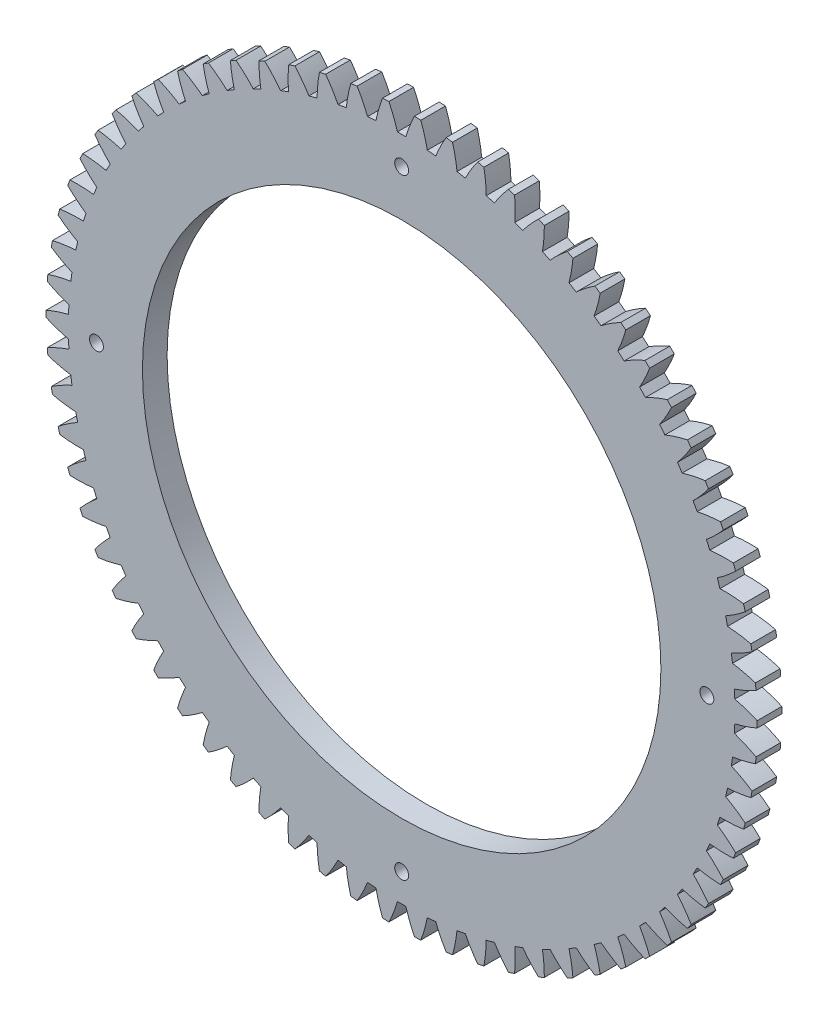
SolidWorks part; units mm, degrees
ref_plane "Front Plane" through (0, 0, 0) normal (0, 0, 1) x (1, 0, 0)
ref_plane "Top Plane" through (0, 0, 0) normal (0, 1, 0) x (1, 0, 0)
ref_plane "Right Plane" through (0, 0, 0) normal (1, 0, 0) x (0, 0, -1)
sketch "Sketch1" plane through (0, 0, 0) normal (0, 0, 1) x (1, 0, 0)
  point P0 (0, 0)
  circle B0 centre (78.5, 0) radius 1.7859
  circle B1 centre (0, -78.5) radius 1.7859
  circle B2 centre (0, 0) radius 66.675
  circle B3 centre (-78.5, 0) radius 1.7859
  circle B4 centre (0, 78.5) radius 1.7859
  arc B5 (-91.4363, -0.8211) -> (-85.6793, -2.7591) centre (-77.2542, 31.7884) ccw
  arc B6 (-85.6793, -2.7591) -> (-85.5817, -4.9322) centre (0, 0) ccw
  arc B7 (-85.5817, -4.9322) -> (-91.1418, -7.3785) centre (-74.0937, -38.5855) ccw
  arc B8 (-91.1418, -7.3785) -> (-90.9946, -9.0141) centre (0, 0) ccw
  arc B9 (-90.9946, -9.0141) -> (-85.0871, -10.4282) centre (-79.7927, 24.7354) ccw
  arc B10 (-85.0871, -10.4282) -> (-84.7951, -12.5839) centre (0, 0) ccw
  arc B11 (-84.7951, -12.5839) -> (-90.1135, -15.5187) centre (-70.3366, -45.0718) ccw
  arc B12 (-90.1135, -15.5187) -> (-89.8203, -17.1345) centre (0, 0) ccw
  arc B13 (-89.8203, -17.1345) -> (-83.8098, -18.0134) centre (-81.6887, 17.4833) ccw
  arc B14 (-83.8098, -18.0134) -> (-83.3257, -20.1342) centre (0, 0) ccw
  arc B15 (-83.3257, -20.1342) -> (-88.3597, -23.5339) centre (-66.0133, -51.1953) ccw
  arc B16 (-88.3597, -23.5339) -> (-87.9228, -25.1169) centre (0, 0) ccw
  arc B17 (-87.9228, -25.1169) -> (-81.8577, -25.4535) centre (-82.927, 10.0904) ccw
  arc B18 (-81.8577, -25.4535) -> (-81.1854, -27.5224) centre (0, 0) ccw
  arc B19 (-81.1854, -27.5224) -> (-85.8944, -31.3597) centre (-61.1584, -56.9066) ccw
  arc B20 (-85.8944, -31.3597) -> (-85.3174, -32.8972) centre (0, 0) ccw
  arc B21 (-85.3174, -32.8972) -> (-79.2465, -32.6887) centre (-83.4977, 2.6163) ccw
  arc B22 (-79.2465, -32.6887) -> (-78.3915, -34.689) centre (0, 0) ccw
  arc B23 (-78.3915, -34.689) -> (-82.7375, -38.9329) centre (-55.8111, -62.1597) ccw
  arc B24 (-82.7375, -38.9329) -> (-82.025, -40.4125) centre (0, 0) ccw
  arc B25 (-82.025, -40.4125) -> (-75.9973, -39.6607) centre (-83.3961, -4.879) ccw
  arc B26 (-75.9973, -39.6607) -> (-74.9664, -41.5763) centre (0, 0) ccw
  arc B27 (-74.9664, -41.5763) -> (-78.9145, -46.1928) centre (-50.0145, -66.9123) ccw
  arc B28 (-78.9145, -46.1928) -> (-78.0723, -47.6025) centre (0, 0) ccw
  arc B29 (-78.0723, -47.6025) -> (-72.1362, -46.3134) centre (-82.623, -12.3349) ccw
  arc B30 (-72.1362, -46.3134) -> (-70.9378, -48.1289) centre (0, 0) ccw
  arc B31 (-70.9378, -48.1289) -> (-74.4562, -53.0806) centre (-43.8152, -71.1262) ccw
  arc B32 (-74.4562, -53.0806) -> (-73.4909, -54.4092) centre (0, 0) ccw
  arc B33 (-73.4909, -54.4092) -> (-67.6943, -52.5932) centre (-81.1847, -19.6915) ccw
  arc B34 (-67.6943, -52.5932) -> (-66.338, -54.2939) centre (0, 0) ccw
  arc B35 (-66.338, -54.2939) -> (-69.3983, -59.5411) centre (-37.2631, -74.7675) ccw
  arc B36 (-69.3983, -59.5411) -> (-68.3178, -60.7778) centre (0, 0) ccw
  arc B37 (-68.3178, -60.7778) -> (-62.7073, -58.4495) centre (-79.0927, -26.8896) ccw
  arc B38 (-62.7073, -58.4495) -> (-61.204, -60.0219) centre (0, 0) ccw
  arc B39 (-61.204, -60.0219) -> (-63.7817, -65.5223) centre (-30.411, -77.8067) ccw
  arc B40 (-63.7817, -65.5223) -> (-62.5947, -66.6571) centre (0, 0) ccw
  arc B41 (-62.5947, -66.6571) -> (-57.2155, -63.8353) centre (-76.364, -33.8711) ccw
  arc B42 (-57.2155, -63.8353) -> (-55.5773, -65.2665) centre (0, 0) ccw
  arc B43 (-55.5773, -65.2665) -> (-57.6516, -70.9758) centre (-23.314, -80.2195) ccw
  arc B44 (-57.6516, -70.9758) -> (-56.3677, -71.9997) centre (0, 0) ccw
  arc B45 (-56.3677, -71.9997) -> (-51.263, -68.7071) centre (-73.0204, -40.58) ccw
  arc B46 (-51.263, -68.7071) -> (-49.5031, -69.9857) centre (0, 0) ccw
  arc B47 (-49.5031, -69.9857) -> (-51.0573, -75.858) centre (-16.0293, -81.9864) ccw
  arc B48 (-51.0573, -75.858) -> (-49.6867, -76.7626) centre (0, 0) ccw
  arc B49 (-49.6867, -76.7626) -> (-44.8978, -73.0256) centre (-69.0889, -46.9621) ccw
  arc B50 (-44.8978, -73.0256) -> (-43.0304, -74.1414) centre (0, 0) ccw
  arc B51 (-43.0304, -74.1414) -> (-44.0519, -80.1293) centre (-8.6156, -83.0932) ccw
  arc B52 (-44.0519, -80.1293) -> (-42.6058, -80.9075) centre (0, 0) ccw
  arc B53 (-42.6058, -80.9075) -> (-38.1711, -76.7563) centre (-64.6011, -52.9661) ccw
  arc B54 (-38.1711, -76.7563) -> (-36.2112, -77.7001) centre (0, 0) ccw
  arc B55 (-36.2112, -77.7001) -> (-36.6918, -83.7555) centre (-1.1325, -83.531) ccw
  arc B56 (-36.6918, -83.7555) -> (-35.1817, -84.4009) centre (0, 0) ccw
  arc B57 (-35.1817, -84.4009) -> (-31.1371, -79.8689) centre (-59.5932, -58.5437) ccw
  arc B58 (-31.1371, -79.8689) -> (-29.1004, -80.6333) centre (0, 0) ccw
  arc B59 (-29.1004, -80.6333) -> (-29.0363, -86.7074) centre (6.3597, -83.2962) ccw
  arc B60 (-29.0363, -86.7074) -> (-27.4745, -87.2148) centre (0, 0) ccw
  arc B61 (-27.4745, -87.2148) -> (-23.8523, -82.3385) centre (-54.1054, -63.6499) ccw
  arc B62 (-23.8523, -82.3385) -> (-21.7554, -82.9172) centre (0, 0) ccw
  arc B63 (-21.7554, -82.9172) -> (-21.147, -88.9611) centre (13.8007, -82.3908) ccw
  arc B64 (-21.147, -88.9611) -> (-19.546, -89.3265) centre (0, 0) ccw
  arc B65 (-19.546, -89.3265) -> (-16.3755, -84.1451) centre (-48.1821, -68.2437) ccw
  arc B66 (-16.3755, -84.1451) -> (-14.2351, -84.5335) centre (0, 0) ccw
  arc B67 (-14.2351, -84.5335) -> (-13.0875, -90.4986) centre (21.1306, -80.8221) ccw
  arc B68 (-13.0875, -90.4986) -> (-11.4601, -90.719) centre (0, 0) ccw
  arc B69 (-11.4601, -90.719) -> (-8.7669, -85.2743) centre (-41.8708, -72.2879) ccw
  arc B70 (-8.7669, -85.2743) -> (-6.6003, -85.4693) centre (0, 0) ccw
  arc B71 (-6.6003, -85.4693) -> (-4.9225, -91.3074) centre (28.2904, -78.6026) ccw
  arc B72 (-4.9225, -91.3074) -> (-3.282, -91.3811) centre (0, 0) ccw
  arc B73 (-3.282, -91.3811) -> (-1.0877, -85.7168) centre (-35.2224, -75.7502) ccw
  arc B74 (-1.0877, -85.7168) -> (1.0877, -85.7168) centre (0, 0) ccw
  arc B75 (1.0877, -85.7168) -> (3.282, -91.3811) centre (35.2224, -75.7502) ccw
  arc B76 (3.282, -91.3811) -> (4.9225, -91.3074) centre (0, 0) ccw
  arc B77 (4.9225, -91.3074) -> (6.6003, -85.4693) centre (-28.2904, -78.6026) ccw
  arc B78 (6.6003, -85.4693) -> (8.7669, -85.2743) centre (0, 0) ccw
  arc B79 (8.7669, -85.2743) -> (11.4601, -90.719) centre (41.8708, -72.2879) ccw
  arc B80 (11.4601, -90.719) -> (13.0875, -90.4986) centre (0, 0) ccw
  arc B81 (13.0875, -90.4986) -> (14.2351, -84.5335) centre (-21.1306, -80.8221) ccw
  arc B82 (14.2351, -84.5335) -> (16.3755, -84.1451) centre (0, 0) ccw
  arc B83 (16.3755, -84.1451) -> (19.546, -89.3265) centre (48.1821, -68.2437) ccw
  arc B84 (19.546, -89.3265) -> (21.147, -88.9611) centre (0, 0) ccw
  arc B85 (21.147, -88.9611) -> (21.7554, -82.9172) centre (-13.8007, -82.3908) ccw
  arc B86 (21.7554, -82.9172) -> (23.8523, -82.3385) centre (0, 0) ccw
  arc B87 (23.8523, -82.3385) -> (27.4745, -87.2148) centre (54.1054, -63.6499) ccw
  arc B88 (27.4745, -87.2148) -> (29.0363, -86.7074) centre (0, 0) ccw
  arc B89 (29.0363, -86.7074) -> (29.1004, -80.6333) centre (-6.3597, -83.2962) ccw
  arc B90 (29.1004, -80.6333) -> (31.1371, -79.8689) centre (0, 0) ccw
  arc B91 (31.1371, -79.8689) -> (35.1817, -84.4009) centre (59.5932, -58.5437) ccw
  arc B92 (35.1817, -84.4009) -> (36.6918, -83.7555) centre (0, 0) ccw
  arc B93 (36.6918, -83.7555) -> (36.2112, -77.7001) centre (1.1325, -83.531) ccw
  arc B94 (36.2112, -77.7001) -> (38.1711, -76.7563) centre (0, 0) ccw
  arc B95 (38.1711, -76.7563) -> (42.6058, -80.9075) centre (64.6011, -52.9661) ccw
  arc B96 (42.6058, -80.9075) -> (44.0519, -80.1293) centre (0, 0) ccw
  arc B97 (44.0519, -80.1293) -> (43.0304, -74.1414) centre (8.6156, -83.0932) ccw
  arc B98 (43.0304, -74.1414) -> (44.8978, -73.0256) centre (0, 0) ccw
  arc B99 (44.8978, -73.0256) -> (49.6867, -76.7626) centre (69.0889, -46.9621) ccw
  arc B100 (49.6867, -76.7626) -> (51.0573, -75.858) centre (0, 0) ccw
  arc B101 (51.0573, -75.858) -> (49.5031, -69.9857) centre (16.0293, -81.9864) ccw
  arc B102 (49.5031, -69.9857) -> (51.263, -68.7071) centre (0, 0) ccw
  arc B103 (51.263, -68.7071) -> (56.3677, -71.9997) centre (73.0204, -40.58) ccw
  arc B104 (56.3677, -71.9997) -> (57.6516, -70.9758) centre (0, 0) ccw
  arc B105 (57.6516, -70.9758) -> (55.5773, -65.2665) centre (23.314, -80.2195) ccw
  arc B106 (55.5773, -65.2665) -> (57.2155, -63.8353) centre (0, 0) ccw
  arc B107 (57.2155, -63.8353) -> (62.5947, -66.6571) centre (76.364, -33.8711) ccw
  arc B108 (62.5947, -66.6571) -> (63.7817, -65.5223) centre (0, 0) ccw
  arc B109 (63.7817, -65.5223) -> (61.204, -60.0219) centre (30.411, -77.8067) ccw
  arc B110 (61.204, -60.0219) -> (62.7073, -58.4495) centre (0, 0) ccw
  arc B111 (62.7073, -58.4495) -> (68.3178, -60.7778) centre (79.0927, -26.8896) ccw
  arc B112 (68.3178, -60.7778) -> (69.3983, -59.5411) centre (0, 0) ccw
  arc B113 (69.3983, -59.5411) -> (66.338, -54.2939) centre (37.2631, -74.7675) ccw
  arc B114 (66.338, -54.2939) -> (67.6943, -52.5932) centre (0, 0) ccw
  arc B115 (67.6943, -52.5932) -> (73.4909, -54.4092) centre (81.1847, -19.6915) ccw
  arc B116 (73.4909, -54.4092) -> (74.4562, -53.0806) centre (0, 0) ccw
  arc B117 (74.4562, -53.0806) -> (70.9378, -48.1289) centre (43.8152, -71.1262) ccw
  arc B118 (70.9378, -48.1289) -> (72.1362, -46.3134) centre (0, 0) ccw
  arc B119 (72.1362, -46.3134) -> (78.0723, -47.6025) centre (82.623, -12.3349) ccw
  arc B120 (78.0723, -47.6025) -> (78.9145, -46.1928) centre (0, 0) ccw
  arc B121 (78.9145, -46.1928) -> (74.9664, -41.5763) centre (50.0145, -66.9123) ccw
  arc B122 (74.9664, -41.5763) -> (75.9973, -39.6607) centre (0, 0) ccw
  arc B123 (75.9973, -39.6607) -> (82.025, -40.4125) centre (83.3961, -4.879) ccw
  arc B124 (82.025, -40.4125) -> (82.7375, -38.9329) centre (0, 0) ccw
  arc B125 (82.7375, -38.9329) -> (78.3915, -34.689) centre (55.8111, -62.1597) ccw
  arc B126 (78.3915, -34.689) -> (79.2465, -32.6887) centre (0, 0) ccw
  arc B127 (79.2465, -32.6887) -> (85.3174, -32.8972) centre (83.4977, 2.6163) ccw
  arc B128 (85.3174, -32.8972) -> (85.8944, -31.3597) centre (0, 0) ccw
  arc B129 (85.8944, -31.3597) -> (81.1854, -27.5224) centre (61.1584, -56.9066) ccw
  arc B130 (81.1854, -27.5224) -> (81.8577, -25.4535) centre (0, 0) ccw
  arc B131 (81.8577, -25.4535) -> (87.9228, -25.1169) centre (82.927, 10.0904) ccw
  arc B132 (87.9228, -25.1169) -> (88.3597, -23.5339) centre (0, 0) ccw
  arc B133 (88.3597, -23.5339) -> (83.3257, -20.1342) centre (66.0133, -51.1953) ccw
  arc B134 (83.3257, -20.1342) -> (83.8098, -18.0134) centre (0, 0) ccw
  arc B135 (83.8098, -18.0134) -> (89.8203, -17.1345) centre (81.6887, 17.4833) ccw
  arc B136 (89.8203, -17.1345) -> (90.1135, -15.5187) centre (0, 0) ccw
  arc B137 (90.1135, -15.5187) -> (84.7951, -12.5839) centre (70.3366, -45.0718) ccw
  arc B138 (84.7951, -12.5839) -> (85.0871, -10.4282) centre (0, 0) ccw
  arc B139 (85.0871, -10.4282) -> (90.9946, -9.0141) centre (79.7927, 24.7354) ccw
  arc B140 (90.9946, -9.0141) -> (91.1418, -7.3785) centre (0, 0) ccw
  arc B141 (91.1418, -7.3785) -> (85.5817, -4.9322) centre (74.0937, -38.5855) ccw
  arc B142 (85.5817, -4.9322) -> (85.6793, -2.7591) centre (0, 0) ccw
  arc B143 (85.6793, -2.7591) -> (91.4363, -0.8211) centre (77.2542, 31.7884) ccw
  arc B144 (91.4363, -0.8211) -> (91.4363, 0.8211) centre (0, 0) ccw
  arc B145 (91.4363, 0.8211) -> (85.6793, 2.7591) centre (77.2542, -31.7884) ccw
  arc B146 (85.6793, 2.7591) -> (85.5817, 4.9322) centre (0, 0) ccw
  arc B147 (85.5817, 4.9322) -> (91.1418, 7.3785) centre (74.0937, 38.5855) ccw
  arc B148 (91.1418, 7.3785) -> (90.9946, 9.0141) centre (0, 0) ccw
  arc B149 (90.9946, 9.0141) -> (85.0871, 10.4282) centre (79.7927, -24.7354) ccw
  arc B150 (85.0871, 10.4282) -> (84.7951, 12.5839) centre (0, 0) ccw
  arc B151 (84.7951, 12.5839) -> (90.1135, 15.5187) centre (70.3366, 45.0718) ccw
  arc B152 (90.1135, 15.5187) -> (89.8203, 17.1345) centre (0, 0) ccw
  arc B153 (89.8203, 17.1345) -> (83.8098, 18.0134) centre (81.6887, -17.4833) ccw
  arc B154 (83.8098, 18.0134) -> (83.3257, 20.1342) centre (0, 0) ccw
  arc B155 (83.3257, 20.1342) -> (88.3597, 23.5339) centre (66.0133, 51.1953) ccw
  arc B156 (88.3597, 23.5339) -> (87.9228, 25.1169) centre (0, 0) ccw
  arc B157 (87.9228, 25.1169) -> (81.8577, 25.4535) centre (82.927, -10.0904) ccw
  arc B158 (81.8577, 25.4535) -> (81.1854, 27.5224) centre (0, 0) ccw
  arc B159 (81.1854, 27.5224) -> (85.8944, 31.3597) centre (61.1584, 56.9066) ccw
  arc B160 (85.8944, 31.3597) -> (85.3174, 32.8972) centre (0, 0) ccw
  arc B161 (85.3174, 32.8972) -> (79.2465, 32.6887) centre (83.4977, -2.6163) ccw
  arc B162 (79.2465, 32.6887) -> (78.3915, 34.689) centre (0, 0) ccw
  arc B163 (78.3915, 34.689) -> (82.7375, 38.9329) centre (55.8111, 62.1597) ccw
  arc B164 (82.7375, 38.9329) -> (82.025, 40.4125) centre (0, 0) ccw
  arc B165 (82.025, 40.4125) -> (75.9973, 39.6607) centre (83.3961, 4.879) ccw
  arc B166 (75.9973, 39.6607) -> (74.9664, 41.5763) centre (0, 0) ccw
  arc B167 (74.9664, 41.5763) -> (78.9145, 46.1928) centre (50.0145, 66.9123) ccw
  arc B168 (78.9145, 46.1928) -> (78.0723, 47.6025) centre (0, 0) ccw
  arc B169 (78.0723, 47.6025) -> (72.1362, 46.3134) centre (82.623, 12.3349) ccw
  arc B170 (72.1362, 46.3134) -> (70.9378, 48.1289) centre (0, 0) ccw
  arc B171 (70.9378, 48.1289) -> (74.4562, 53.0806) centre (43.8152, 71.1262) ccw
  arc B172 (74.4562, 53.0806) -> (73.4909, 54.4092) centre (0, 0) ccw
  arc B173 (73.4909, 54.4092) -> (67.6943, 52.5932) centre (81.1847, 19.6915) ccw
  arc B174 (67.6943, 52.5932) -> (66.338, 54.2939) centre (0, 0) ccw
  arc B175 (66.338, 54.2939) -> (69.3983, 59.5411) centre (37.2631, 74.7675) ccw
  arc B176 (69.3983, 59.5411) -> (68.3178, 60.7778) centre (0, 0) ccw
  arc B177 (68.3178, 60.7778) -> (62.7073, 58.4495) centre (79.0927, 26.8896) ccw
  arc B178 (62.7073, 58.4495) -> (61.204, 60.0219) centre (0, 0) ccw
  arc B179 (61.204, 60.0219) -> (63.7817, 65.5223) centre (30.411, 77.8067) ccw
  arc B180 (63.7817, 65.5223) -> (62.5947, 66.6571) centre (0, 0) ccw
  arc B181 (62.5947, 66.6571) -> (57.2155, 63.8353) centre (76.364, 33.8711) ccw
  arc B182 (57.2155, 63.8353) -> (55.5773, 65.2665) centre (0, 0) ccw
  arc B183 (55.5773, 65.2665) -> (57.6516, 70.9758) centre (23.314, 80.2195) ccw
  arc B184 (57.6516, 70.9758) -> (56.3677, 71.9997) centre (0, 0) ccw
  arc B185 (56.3677, 71.9997) -> (51.263, 68.7071) centre (73.0204, 40.58) ccw
  arc B186 (51.263, 68.7071) -> (49.5031, 69.9857) centre (0, 0) ccw
  arc B187 (49.5031, 69.9857) -> (51.0573, 75.858) centre (16.0293, 81.9864) ccw
  arc B188 (51.0573, 75.858) -> (49.6867, 76.7626) centre (0, 0) ccw
  arc B189 (49.6867, 76.7626) -> (44.8978, 73.0256) centre (69.0889, 46.9621) ccw
  arc B190 (44.8978, 73.0256) -> (43.0304, 74.1414) centre (0, 0) ccw
  arc B191 (43.0304, 74.1414) -> (44.0519, 80.1293) centre (8.6156, 83.0932) ccw
  arc B192 (44.0519, 80.1293) -> (42.6058, 80.9075) centre (0, 0) ccw
  arc B193 (42.6058, 80.9075) -> (38.1711, 76.7563) centre (64.6011, 52.9661) ccw
  arc B194 (38.1711, 76.7563) -> (36.2112, 77.7001) centre (0, 0) ccw
  arc B195 (36.2112, 77.7001) -> (36.6918, 83.7555) centre (1.1325, 83.531) ccw
  arc B196 (36.6918, 83.7555) -> (35.1817, 84.4009) centre (0, 0) ccw
  arc B197 (35.1817, 84.4009) -> (31.1371, 79.8689) centre (59.5932, 58.5437) ccw
  arc B198 (31.1371, 79.8689) -> (29.1004, 80.6333) centre (0, 0) ccw
  arc B199 (29.1004, 80.6333) -> (29.0363, 86.7074) centre (-6.3597, 83.2962) ccw
  arc B200 (29.0363, 86.7074) -> (27.4745, 87.2148) centre (0, 0) ccw
  arc B201 (27.4745, 87.2148) -> (23.8523, 82.3385) centre (54.1054, 63.6499) ccw
  arc B202 (23.8523, 82.3385) -> (21.7554, 82.9172) centre (0, 0) ccw
  arc B203 (21.7554, 82.9172) -> (21.147, 88.9611) centre (-13.8007, 82.3908) ccw
  arc B204 (21.147, 88.9611) -> (19.546, 89.3265) centre (0, 0) ccw
  arc B205 (19.546, 89.3265) -> (16.3755, 84.1451) centre (48.1821, 68.2437) ccw
  arc B206 (16.3755, 84.1451) -> (14.2351, 84.5335) centre (0, 0) ccw
  arc B207 (14.2351, 84.5335) -> (13.0875, 90.4986) centre (-21.1306, 80.8221) ccw
  arc B208 (13.0875, 90.4986) -> (11.4601, 90.719) centre (0, 0) ccw
  arc B209 (11.4601, 90.719) -> (8.7669, 85.2743) centre (41.8708, 72.2879) ccw
  arc B210 (8.7669, 85.2743) -> (6.6003, 85.4693) centre (0, 0) ccw
  arc B211 (6.6003, 85.4693) -> (4.9225, 91.3074) centre (-28.2904, 78.6026) ccw
  arc B212 (4.9225, 91.3074) -> (3.282, 91.3811) centre (0, 0) ccw
  arc B213 (3.282, 91.3811) -> (1.0877, 85.7168) centre (35.2224, 75.7502) ccw
  arc B214 (1.0877, 85.7168) -> (-1.0877, 85.7168) centre (0, 0) ccw
  arc B215 (-1.0877, 85.7168) -> (-3.282, 91.3811) centre (-35.2224, 75.7502) ccw
  arc B216 (-3.282, 91.3811) -> (-4.9225, 91.3074) centre (0, 0) ccw
  arc B217 (-4.9225, 91.3074) -> (-6.6003, 85.4693) centre (28.2904, 78.6026) ccw
  arc B218 (-6.6003, 85.4693) -> (-8.7669, 85.2743) centre (0, 0) ccw
  arc B219 (-8.7669, 85.2743) -> (-11.4601, 90.719) centre (-41.8708, 72.2879) ccw
  arc B220 (-11.4601, 90.719) -> (-13.0875, 90.4986) centre (0, 0) ccw
  arc B221 (-13.0875, 90.4986) -> (-14.2351, 84.5335) centre (21.1306, 80.8221) ccw
  arc B222 (-14.2351, 84.5335) -> (-16.3755, 84.1451) centre (0, 0) ccw
  arc B223 (-16.3755, 84.1451) -> (-19.546, 89.3265) centre (-48.1821, 68.2437) ccw
  arc B224 (-19.546, 89.3265) -> (-21.147, 88.9611) centre (0, 0) ccw
  arc B225 (-21.147, 88.9611) -> (-21.7554, 82.9172) centre (13.8007, 82.3908) ccw
  arc B226 (-21.7554, 82.9172) -> (-23.8523, 82.3385) centre (0, 0) ccw
  arc B227 (-23.8523, 82.3385) -> (-27.4745, 87.2148) centre (-54.1054, 63.6499) ccw
  arc B228 (-27.4745, 87.2148) -> (-29.0363, 86.7074) centre (0, 0) ccw
  arc B229 (-29.0363, 86.7074) -> (-29.1004, 80.6333) centre (6.3597, 83.2962) ccw
  arc B230 (-29.1004, 80.6333) -> (-31.1371, 79.8689) centre (0, 0) ccw
  arc B231 (-31.1371, 79.8689) -> (-35.1817, 84.4009) centre (-59.5932, 58.5437) ccw
  arc B232 (-35.1817, 84.4009) -> (-36.6918, 83.7555) centre (0, 0) ccw
  arc B233 (-36.6918, 83.7555) -> (-36.2112, 77.7001) centre (-1.1325, 83.531) ccw
  arc B234 (-36.2112, 77.7001) -> (-38.1711, 76.7563) centre (0, 0) ccw
  arc B235 (-38.1711, 76.7563) -> (-42.6058, 80.9075) centre (-64.6011, 52.9661) ccw
  arc B236 (-42.6058, 80.9075) -> (-44.0519, 80.1293) centre (0, 0) ccw
  arc B237 (-44.0519, 80.1293) -> (-43.0304, 74.1414) centre (-8.6156, 83.0932) ccw
  arc B238 (-43.0304, 74.1414) -> (-44.8978, 73.0256) centre (0, 0) ccw
  arc B239 (-44.8978, 73.0256) -> (-49.6867, 76.7626) centre (-69.0889, 46.9621) ccw
  arc B240 (-49.6867, 76.7626) -> (-51.0573, 75.858) centre (0, 0) ccw
  arc B241 (-51.0573, 75.858) -> (-49.5031, 69.9857) centre (-16.0293, 81.9864) ccw
  arc B242 (-49.5031, 69.9857) -> (-51.263, 68.7071) centre (0, 0) ccw
  arc B243 (-51.263, 68.7071) -> (-56.3677, 71.9997) centre (-73.0204, 40.58) ccw
  arc B244 (-56.3677, 71.9997) -> (-57.6516, 70.9758) centre (0, 0) ccw
  arc B245 (-57.6516, 70.9758) -> (-55.5773, 65.2665) centre (-23.314, 80.2195) ccw
  arc B246 (-55.5773, 65.2665) -> (-57.2155, 63.8353) centre (0, 0) ccw
  arc B247 (-57.2155, 63.8353) -> (-62.5947, 66.6571) centre (-76.364, 33.8711) ccw
  arc B248 (-62.5947, 66.6571) -> (-63.7817, 65.5223) centre (0, 0) ccw
  arc B249 (-63.7817, 65.5223) -> (-61.204, 60.0219) centre (-30.411, 77.8067) ccw
  arc B250 (-61.204, 60.0219) -> (-62.7073, 58.4495) centre (0, 0) ccw
  arc B251 (-62.7073, 58.4495) -> (-68.3178, 60.7778) centre (-79.0927, 26.8896) ccw
  arc B252 (-68.3178, 60.7778) -> (-69.3983, 59.5411) centre (0, 0) ccw
  arc B253 (-69.3983, 59.5411) -> (-66.338, 54.2939) centre (-37.2631, 74.7675) ccw
  arc B254 (-66.338, 54.2939) -> (-67.6943, 52.5932) centre (0, 0) ccw
  arc B255 (-67.6943, 52.5932) -> (-73.4909, 54.4092) centre (-81.1847, 19.6915) ccw
  arc B256 (-73.4909, 54.4092) -> (-74.4562, 53.0806) centre (0, 0) ccw
  arc B257 (-74.4562, 53.0806) -> (-70.9378, 48.1289) centre (-43.8152, 71.1262) ccw
  arc B258 (-70.9378, 48.1289) -> (-72.1362, 46.3134) centre (0, 0) ccw
  arc B259 (-72.1362, 46.3134) -> (-78.0723, 47.6025) centre (-82.623, 12.3349) ccw
  arc B260 (-78.0723, 47.6025) -> (-78.9145, 46.1928) centre (0, 0) ccw
  arc B261 (-78.9145, 46.1928) -> (-74.9664, 41.5763) centre (-50.0145, 66.9123) ccw
  arc B262 (-74.9664, 41.5763) -> (-75.9973, 39.6607) centre (0, 0) ccw
  arc B263 (-75.9973, 39.6607) -> (-82.025, 40.4125) centre (-83.3961, 4.879) ccw
  arc B264 (-82.025, 40.4125) -> (-82.7375, 38.9329) centre (0, 0) ccw
  arc B265 (-82.7375, 38.9329) -> (-78.3915, 34.689) centre (-55.8111, 62.1597) ccw
  arc B266 (-78.3915, 34.689) -> (-79.2465, 32.6887) centre (0, 0) ccw
  arc B267 (-79.2465, 32.6887) -> (-85.3174, 32.8972) centre (-83.4977, -2.6163) ccw
  arc B268 (-85.3174, 32.8972) -> (-85.8944, 31.3597) centre (0, 0) ccw
  arc B269 (-85.8944, 31.3597) -> (-81.1854, 27.5224) centre (-61.1584, 56.9066) ccw
  arc B270 (-81.1854, 27.5224) -> (-81.8577, 25.4535) centre (0, 0) ccw
  arc B271 (-81.8577, 25.4535) -> (-87.9228, 25.1169) centre (-82.927, -10.0904) ccw
  arc B272 (-87.9228, 25.1169) -> (-88.3597, 23.5339) centre (0, 0) ccw
  arc B273 (-88.3597, 23.5339) -> (-83.3257, 20.1342) centre (-66.0133, 51.1953) ccw
  arc B274 (-83.3257, 20.1342) -> (-83.8098, 18.0134) centre (0, 0) ccw
  arc B275 (-83.8098, 18.0134) -> (-89.8203, 17.1345) centre (-81.6887, -17.4833) ccw
  arc B276 (-89.8203, 17.1345) -> (-90.1135, 15.5187) centre (0, 0) ccw
  arc B277 (-90.1135, 15.5187) -> (-84.7951, 12.5839) centre (-70.3366, 45.0718) ccw
  arc B278 (-84.7951, 12.5839) -> (-85.0871, 10.4282) centre (0, 0) ccw
  arc B279 (-85.0871, 10.4282) -> (-90.9946, 9.0141) centre (-79.7927, -24.7354) ccw
  arc B280 (-90.9946, 9.0141) -> (-91.1418, 7.3785) centre (0, 0) ccw
  arc B281 (-91.1418, 7.3785) -> (-85.5817, 4.9322) centre (-74.0937, 38.5855) ccw
  arc B282 (-85.5817, 4.9322) -> (-85.6793, 2.7591) centre (0, 0) ccw
  arc B283 (-85.6793, 2.7591) -> (-91.4363, 0.8211) centre (-77.2542, -31.7884) ccw
  arc B284 (-91.4363, 0.8211) -> (-91.4363, -0.8211) centre (0, 0) ccw
sketch_block_instance "HG_Gear_2-1"
sketch_block "HG_Gear_2"
extrude "Boss-Extrude1" add sketch "Sketch1" along normal blind 6.35
